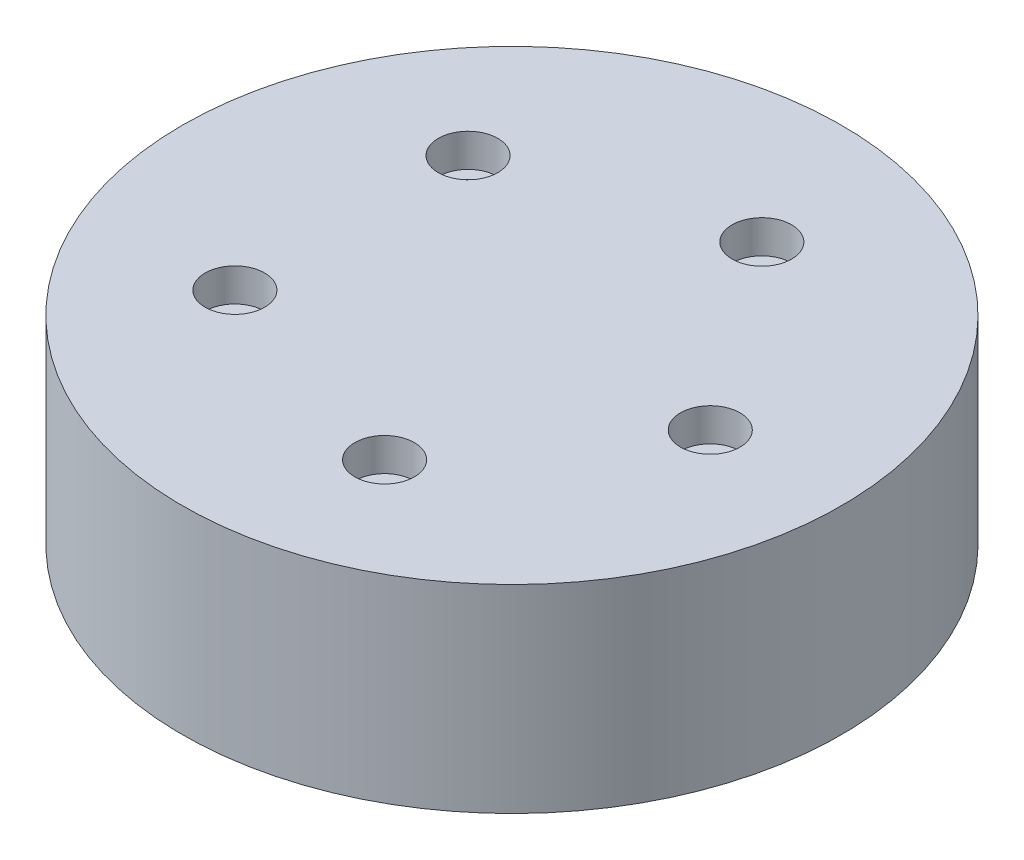
SolidWorks part; units mm, degrees
ref_plane "Front Plane" through (0, 0, 0) normal (0, 0, 1) x (1, 0, 0)
ref_plane "Top Plane" through (0, 0, 0) normal (0, 1, 0) x (1, 0, 0)
ref_plane "Right Plane" through (0, 0, 0) normal (1, 0, 0) x (0, 0, -1)
sketch "Sketch3" plane through (0, 15, 0) normal (0, 1, 0) x (1, 0, 0)
  circle A0 centre (-1.2, 0) radius 24.925
  circle A1 centre (13.8, 0) radius 1.3
  circle A6 centre (-1.2, 0) radius 15
  circle A7 centre (-1.2, 0) radius 15
  circle A8 centre (3.4353, -14.2658) radius 1.3
  circle A9 centre (-1.2, 0) radius 15
  circle A10 centre (-13.3353, -8.8168) radius 1.3
  circle A11 centre (-1.2, 0) radius 15
  circle A12 centre (-13.3353, 8.8168) radius 1.3
  circle A13 centre (-1.2, 0) radius 15
  circle A14 centre (3.4353, 14.2658) radius 1.3
  dimension "D1" = 49.85
  dimension "D2" = 5
  dimension "D3" = 2.6
extrude "Boss-Extrude1" add sketch "Sketch3" along normal blind 5 and the other way blind 10 contours A14 A6 A12 A10 A8 A1 | A0 A14 A6 A1 A8 A10 A12
sketch "Sketch6" plane through (0, 5, 0) normal (0, -1, 0) x (1, 0, 0)
  circle A0 centre (-1.2, 0) radius 15
  circle A1 centre (13.8, 0) radius 1.65
  circle A2 centre (3.4353, -14.2658) radius 1.65
  circle A3 centre (-13.3353, -8.8168) radius 1.65
  circle A4 centre (-13.3353, 8.8168) radius 1.65
  circle A5 centre (3.4353, 14.2658) radius 1.65
  dimension "D1" = 5
  dimension "D2" = 3.3
extrude "Cut-Extrude1" cut sketch "Sketch6" against normal blind 5 contours A4 | A5 | A1 | A3 | A2
hole_wizard "CBORE for M2.5 SHCS1" positions "Sketch7" profile "Sketch8" counterbore size "M2.5" standard "ANSI Metric" end condition through all
sketch "Sketch7" plane through (0, 20, 0) normal (0, 1, 0) x (1, 0, 0)
  point P0 (13.8, 0)
  point P3 (3.4353, -14.2658)
  point P6 (-13.3353, -8.8168)
  point P9 (3.4353, 14.2658)
  point P12 (-13.3353, 8.8168)
sketch "Sketch8" plane through (13.8, 20, 0) normal (1, 0, 0) x (0, 0, 1)
  line L0 (0, 0) -> (0, 15)
  line L1 (0, 15) -> (1.25, 15)
  line L3 (1.25, 15) -> (1.25, 2.5)
  line L4 (1.25, 2.5) -> (2.25, 2.5)
  line L5 (2.25, 2.5) -> (2.25, 0)
  line L7 (2.25, 0) -> (0, 0)
  line L11 (0, -6.35) -> (0, 107.95) construction
  dimension "Thru Hole Dia." = 2.5
  dimension "Thru Hole Depth" = 15
  dimension "C'Bore Dia." = 4.5
  dimension "C'Bore Depth" = 2.5
